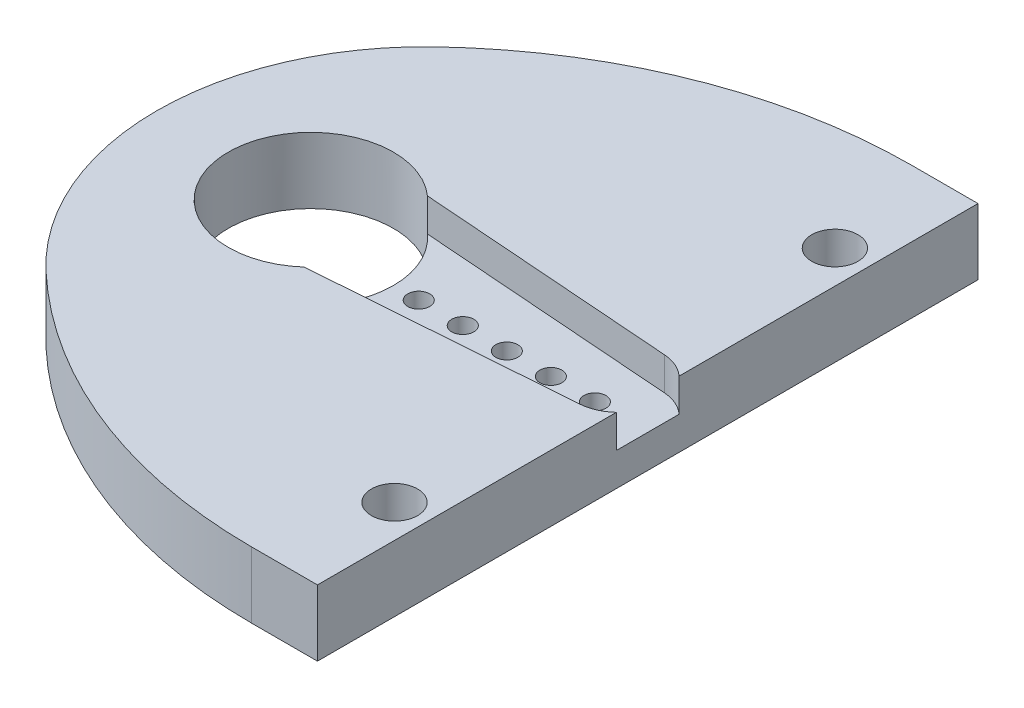
SolidWorks part; units mm, degrees
material "ABS"
ref_plane "Front Plane" through (0, 0, 0) normal (0, 0, 1) x (1, 0, 0)
ref_plane "Top Plane" through (0, 0, 0) normal (0, 1, 0) x (1, 0, 0)
ref_plane "Right Plane" through (0, 0, 0) normal (1, 0, 0) x (0, 0, -1)
sketch "Sketch1" plane through (0, 0, 0) normal (0, 1, 0) x (1, 0, 0)
  line L0 (0, 0) -> (11.2501, 0) construction
  line L1 (-3.2, -8.8283) -> (-3.2, 8.8283) construction
  line L12 (-7, 15) -> (15.3, 15)
  line L13 (-7, 15) -> (-7, -15)
  line L14 (-7, -15) -> (15.3, -15)
  line L15 (15.3, 15) -> (15.3, -15)
  line L16 (12.3, -15) -> (15.3, -15) construction
  line L17 (15.3, 15) -> (12.3, 15)
  line L18 (15.3, 15) -> (15.3, -15)
  line L19 (15.3, -15) -> (12.3, -15)
  line L20 (12.3, 15) -> (12.3, -15)
  line L21 (13.8, -15) -> (13.8, 15) construction
  circle A13 centre (0, 0) radius 2.35
  circle A14 centre (13.8, 10) radius 1.05
  circle A15 centre (13.8, -10) radius 1.05
  arc A16 (12.3, -15) -> (-3.2, -8.8283) centre (12.3, 7.5496) cw
  arc A17 (12.3, 15) -> (-3.2, 8.8283) centre (12.3, -7.5496) ccw
  arc A18 (-3.2, 8.8283) -> (-3.2, -8.8283) centre (5.1551, 0) ccw
  dimension "D4" = 30
  dimension "D6" = 17
  dimension "D5" = 2.1
  dimension "D13" = 20
  dimension "D3" = 2.1
  dimension "D2" = 4.7
  dimension "D10" = 22.3
  dimension "D11" = 7
  dimension "D12" = 3
extrude "Boss-Extrude1" add sketch "Sketch1" against normal blind 3
sketch "Esquisse1" plane through (0, 0, 0) normal (0, 1, 0) x (1, 0, 0)
  line L2 (2.4945, -2.8) -> (14.1314, -1.9323)
  line L3 (14.1314, 1.9323) -> (2.4945, 2.8)
  line L4 (2.4945, -2.8) -> (14.1314, -1.9323)
  line L5 (14.1314, 1.9323) -> (2.4945, 2.8)
  arc A1 (2.4945, 2.8) -> (2.4945, -2.8) centre (0, 0) ccw
  arc A2 (2.4945, 2.8) -> (2.4945, -2.8) centre (0, 0) ccw
  spline S1 degree 2 poles (-4147.8221, 14406.5608) (-94.9542, -54.5356) (14.8275, -1.7461) (15.1573, -1.5874) (15.4072, -1.3186) (15.6562, -1.0506) (15.7906, -0.7092) (15.9249, -0.3678) (15.925, 0) (15.9251, 0.3662) (15.791, 0.708) (15.6574, 1.0487) (15.4078, 1.3179) (15.1591, 1.5861) (14.8286, 1.7455) (-94.6633, 54.5525) (-4259.6785, -14373.7657) knots -41.433061 -41.433061 -41.433061 0.125 0.125 0.25 0.25 0.375 0.375 0.5 0.5 0.625 0.625 0.75 0.75 0.875 0.875 42.328322 42.328322 42.328322 only from (14.1314, -1.9323) to (14.1314, 1.9323)
  spline S2 degree 2 poles (14.1314, -1.9323) (14.4973, -1.9048) (14.8275, -1.7461) (15.1573, -1.5874) (15.4072, -1.3186) (15.6562, -1.0506) (15.7906, -0.7092) (15.9249, -0.3678) (15.925, 0) (15.9251, 0.3662) (15.791, 0.708) (15.6574, 1.0487) (15.4078, 1.3179) (15.1591, 1.5861) (14.8286, 1.7455) (14.4984, 1.9047) (14.1314, 1.9323) knots 0 0 0 0.125 0.125 0.25 0.25 0.375 0.375 0.5 0.5 0.625 0.625 0.75 0.75 0.875 0.875 1 1 1
  dimension "D1" = 0
extrude "Enlèv. mat.-Extru.1" cut sketch "Esquisse1" against normal blind 1.5
sketch "Esquisse3" plane through (0, -1.5, 0) normal (0, 1, 0) x (1, 0, 0)
  circle A0 centre (4.9, 0) radius 0.5 construction
  circle A1 centre (6.9, 0) radius 0.5 construction
  circle A2 centre (8.9, 0) radius 0.5 construction
  circle A3 centre (10.9, 0) radius 0.5 construction
  circle A4 centre (12.9, 0) radius 0.5 construction
  circle A6 centre (4.9, 0) radius 0.5
  circle A7 centre (6.9, 0) radius 0.5
  circle A8 centre (8.9, 0) radius 0.5
  circle A9 centre (10.9, 0) radius 0.5
  circle A10 centre (12.9, 0) radius 0.5
  circle A11 centre (0, 0) radius 3.75
  arc A12 (2.4945, 2.8) -> (2.4945, -2.8) centre (0, 0) ccw construction
extrude "Enlèv. mat.-Extru.7" cut sketch "Esquisse3" against normal through all
